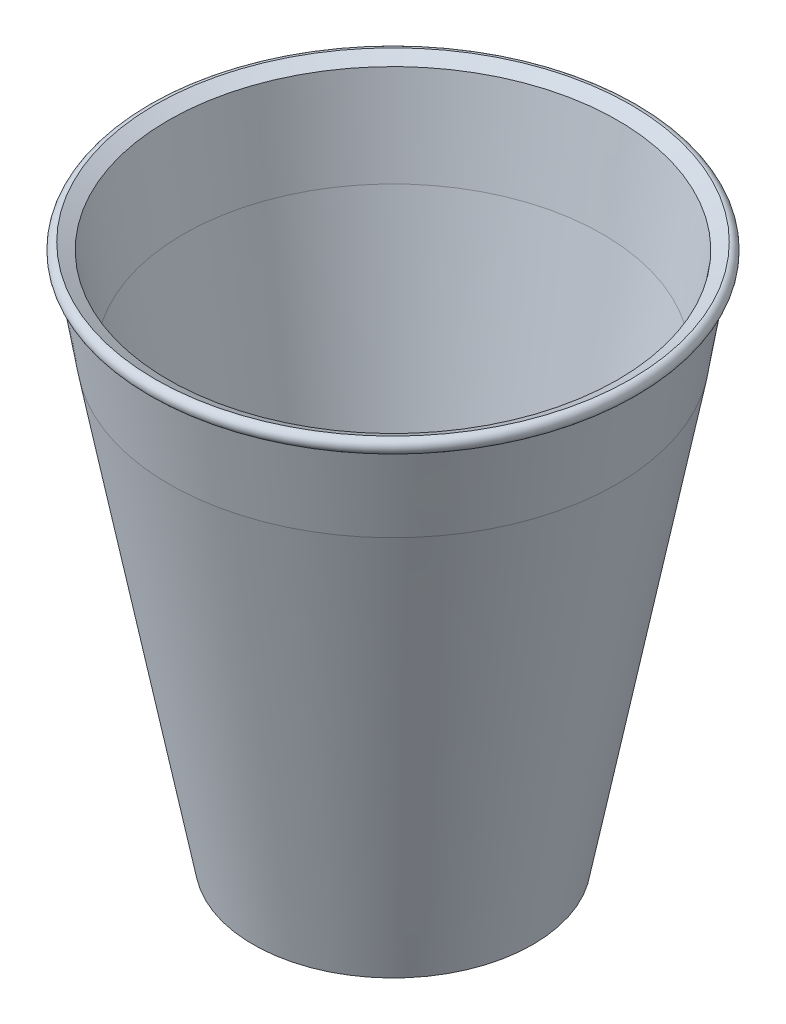
SolidWorks part; units mm, degrees
ref_plane "Front Plane" through (0, 0, 0) normal (0, 0, 1) x (1, 0, 0)
ref_plane "Top Plane" through (0, 0, 0) normal (0, 1, 0) x (1, 0, 0)
ref_plane "Right Plane" through (0, 0, 0) normal (1, 0, 0) x (0, 0, -1)
sketch "Sketch1" plane through (0, 0, 0) normal (0, 0, 1) x (1, 0, 0)
  line L0 (0, 0) -> (0, -77) construction
  line L1 (-20, -77) -> (20, -77) construction
  line L2 (-34, 0) -> (34, 0) construction
  line L3 (-32.1307, -1) -> (-34, 0)
  line L6 (21.5561, -64) -> (20, -77) construction
  line L9 (-34, -2) -> (34, -2) construction
  line L10 (-35, -1) -> (35, -1) construction
  line L11 (-32, -14) -> (32, -14) construction
  line L12 (-34, -2) -> (-32, -14)
  line L15 (34, -2) -> (32, -14) construction
  line L16 (32, -14) -> (27.5, -50.547) construction
  line L17 (27.5, -50.547) -> (23.9354, -64) construction
  line L19 (21.5561, -64) -> (23.9354, -64) construction
  line L22 (0, -74) -> (-18.5355, -74)
  line L27 (-29.964, -14) -> (-32.1307, -1)
  line L28 (-29.964, -14) -> (-18.5355, -74)
  line L29 (-20, -77) -> (-12.6, -77)
  line L30 (-12.6, -77) -> (-12.6, -75.97)
  line L31 (-12.6, -75.97) -> (0, -75.97)
  line L32 (0, -75.97) -> (0, -74)
  line L33 (-32, -14) -> (-20, -77)
  arc A0 (-34, -2) -> (-34, 0) centre (-34, -1) cw
  arc A1 (34, -2) -> (34, 0) centre (34, -1) ccw construction
  point P6 (0, -77)
  point P11 (0, 0)
  point P22 (0, -2)
  point P25 (0, -1)
  point P28 (0, -14)
  dimension "D1" = 77
  dimension "D2" = 40
  dimension "D3" = 68
  dimension "D5" = 2
  dimension "D9" = 2
  dimension "D10" = 68
  dimension "D11" = 70
  dimension "D12" = 1
  dimension "D13" = 14
  dimension "D14" = 64
  dimension "D15" = 1.03
  dimension "D20" = 12.6
  dimension "D21" = 3
revolve "Revolve1" add sketch "Sketch1" angle 360 about L0
